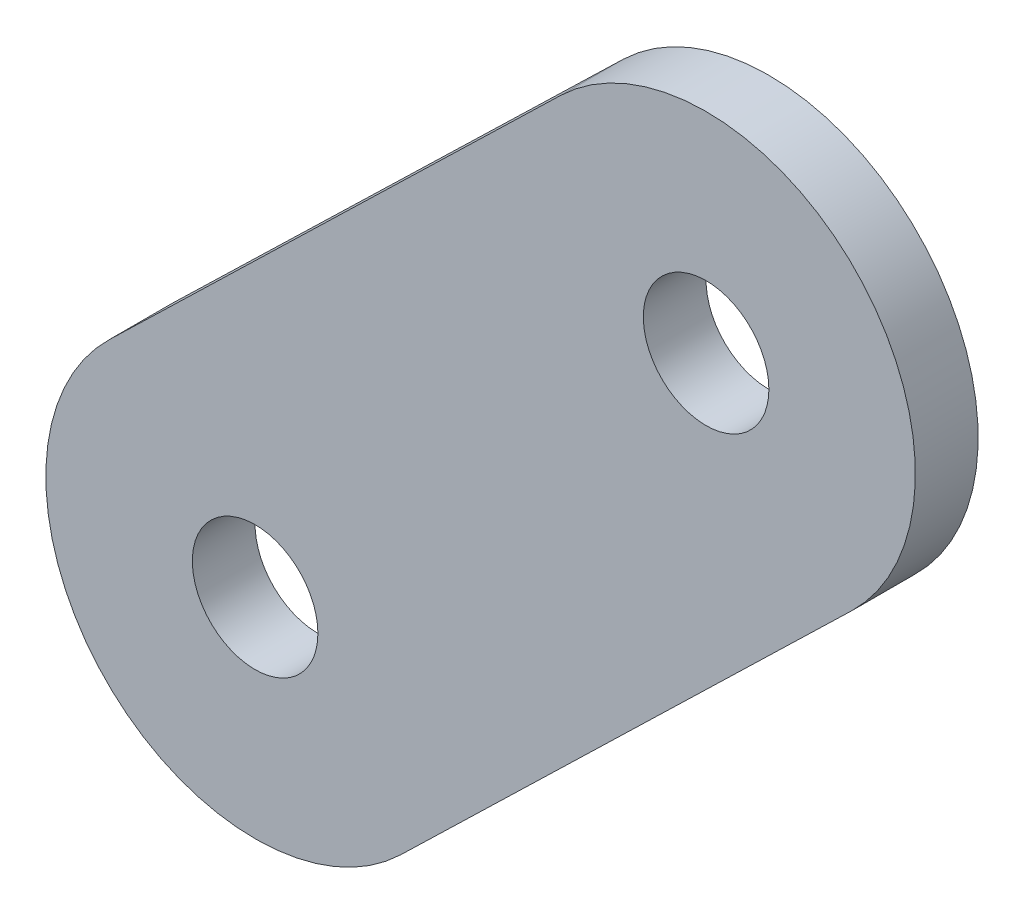
SolidWorks part; units mm, degrees
ref_plane "Front Plane" through (0, 0, 0) normal (0, 0, 1) x (1, 0, 0)
ref_plane "Top Plane" through (0, 0, 0) normal (0, 1, 0) x (1, 0, 0)
ref_plane "Right Plane" through (0, 0, 0) normal (1, 0, 0) x (0, 0, -1)
sketch "Sketch1" plane through (0, 0, 0) normal (0, 0, 1) x (1, 0, 0)
  line L0 (24.1546, 42.4771) -> (145.906, -83.2273) construction
  line L1 (31.1118, 35.294) -> (52.6611, 56.1656)
  line L2 (17.1974, 49.6602) -> (38.7467, 70.5319)
  circle A0 centre (24.1546, 42.4771) radius 3
  arc A1 (17.1974, 49.6602) -> (31.1118, 35.294) centre (24.1546, 42.4771) ccw
  arc A2 (52.6611, 56.1656) -> (38.7467, 70.5319) centre (45.7039, 63.3488) ccw
  circle A3 centre (45.7039, 63.3488) radius 3
extrude "Boss-Extrude1" add sketch "Sketch1" along normal blind 3 contours A2 L2 A1 L1
